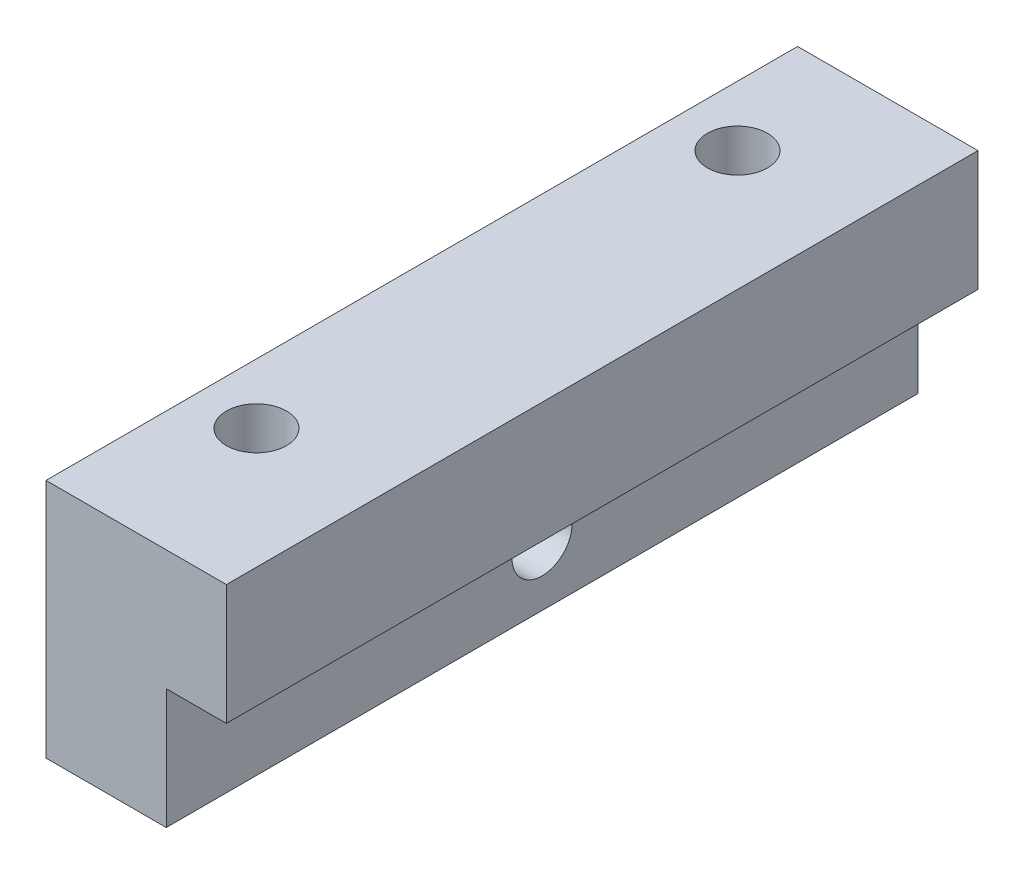
SolidWorks part; units mm, degrees
ref_plane "Front Plane" through (0, 0, 0) normal (0, 0, 1) x (1, 0, 0)
ref_plane "Top Plane" through (0, 0, 0) normal (0, 1, 0) x (1, 0, 0)
ref_plane "Right Plane" through (0, 0, 0) normal (1, 0, 0) x (0, 0, -1)
sketch "Sketch1" plane through (0, 0, 0) normal (0, 0, 1) x (1, 0, 0)
  line L0 (0, 0) -> (0, 16)
  line L1 (0, 16) -> (12, 16)
  line L2 (12, 16) -> (12, 8)
  line L3 (12, 8) -> (8, 8)
  line L4 (8, 8) -> (8, 0)
  line L5 (8, 0) -> (0, 0)
  dimension "D1" = 16
  dimension "D2" = 8
  dimension "D3" = 12
  dimension "D4" = 8
extrude "Boss-Extrude1" add sketch "Sketch1" along normal mid plane 50
sketch "Sketch2" plane through (0, 0, 0) normal (-1, 0, 0) x (0, 0, 1)
  line L0 (25, 16) -> (25, 0) construction
  line L1 (25, 16) -> (-25, 16) construction
  circle A0 centre (0, 4) radius 2
  dimension "D3" = 4
  dimension "D1" = 25
  dimension "D2" = 12
extrude "Cut-Extrude1" cut sketch "Sketch2" against normal blind 50
sketch "Sketch4" plane through (0, 16, 0) normal (0, 1, 0) x (1, 0, 0)
  line L0 (4, 25) -> (4, -25) construction
  line L1 (12, 25) -> (0, 25) construction
  line L2 (12, -25) -> (0, -25) construction
  line L3 (12, 17) -> (0, 17) construction
  line L4 (12, -25) -> (12, 25) construction
  line L5 (0, -25) -> (0, 25) construction
  line L6 (12, -15) -> (0, -15) construction
  circle A0 centre (4, 17) radius 2
  circle A1 centre (4, -15) radius 2
  point P18 (0, 0)
  point P19 (0, 0)
  point P20 (0, 0)
  point P21 (0, 0)
  dimension "D4" = 4
  dimension "D1" = 4
  dimension "D2" = 10
  dimension "D3" = 8
sketch "Sketch5" plane through (0, 0, 25) normal (0, 0, 1) x (1, 0, 0)
  line L0 (4, 0) -> (4, 16) construction
  line L1 (0, 0) -> (8, 0) construction
  line L2 (12, 16) -> (0, 16) construction
extrude "Cut-Extrude2" cut sketch "Sketch4" against normal blind 50
